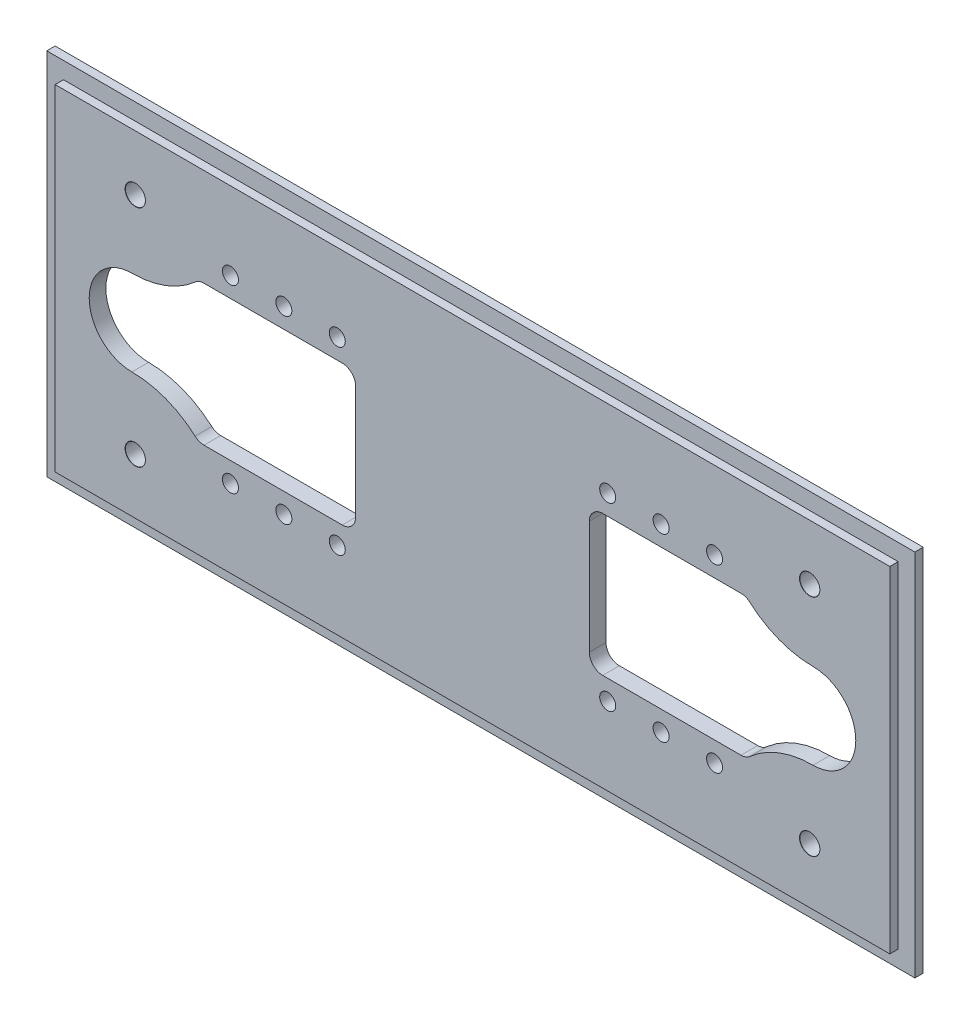
SolidWorks part; units mm, degrees
ref_plane "Plano frontal" through (0, 0, 0) normal (0, 0, 1) x (1, 0, 0)
ref_plane "Plano superior" through (0, 0, 0) normal (0, 1, 0) x (1, 0, 0)
ref_plane "Plano direito" through (0, 0, 0) normal (1, 0, 0) x (0, 0, -1)
sketch "Esboço1" plane through (0, 0, 0) normal (0, 0, 1) x (1, 0, 0)
  line L1 (-63.2916, 33.3513) -> (66.7084, 33.3513)
  line L2 (-63.2916, 33.3513) -> (-63.2916, -21.8987)
  line L3 (-63.2916, -21.8987) -> (66.7084, -21.8987)
  line L4 (66.7084, 33.3513) -> (66.7084, -21.8987)
  dimension "D1" = 130
  dimension "D2" = 55.25
extrude "Ressalto-extrusão1" add sketch "Esboço1" along normal blind 2.5
sketch "Esboço2" plane through (0, 0, 2.5) normal (0, 0, 1) x (1, 0, 0)
  line L0 (1.7084, 33.3513) -> (1.7084, -21.8987) construction
  line L1 (66.7084, 33.3513) -> (-63.2916, 33.3513) construction
  line L2 (-63.2916, -21.8987) -> (66.7084, -21.8987) construction
  line L11 (-54.581, 33.3513) -> (-54.581, -21.8987) construction
  line L13 (-63.2916, 33.3513) -> (66.7084, 33.3513)
  line L14 (-63.2916, 33.3513) -> (-63.2916, -21.8987)
  line L15 (-63.2916, -21.8987) -> (66.7084, -21.8987)
  line L16 (66.7084, 33.3513) -> (66.7084, -21.8987)
  line L17 (-60.7916, 30.8513) -> (64.2084, 30.8513)
  line L18 (-60.7916, 30.8513) -> (-60.7916, -19.3987)
  line L19 (-60.7916, -19.3987) -> (64.2084, -19.3987)
  line L20 (64.2084, 30.8513) -> (64.2084, -19.3987)
  dimension "D1" = 2.5
  dimension "D2" = 2.5
  dimension "D3" = 2.5
  dimension "D4" = 2.5
extrude "Corte-extrusão1" cut sketch "Esboço2" against normal blind 1.25
sketch "Esboço3" plane through (0, 0, 2.5) normal (0, 0, 1) x (1, 0, 0)
  line L0 (-48.7916, 30.8513) -> (-48.7916, -19.3987) construction
  line L1 (64.2084, 30.8513) -> (-60.7916, 30.8513) construction
  line L2 (-60.7916, -19.3987) -> (64.2084, -19.3987) construction
  line L3 (-60.7916, 30.8513) -> (-60.7916, -19.3987) construction
  line L4 (1.7084, 30.8513) -> (1.7084, -19.3987) construction
  line L5 (-60.7916, 5.7263) -> (1.7084, 5.7263) construction
  circle A0 centre (-48.7916, 22.5513) radius 2.75
  circle A1 centre (-48.7916, -11.0987) radius 2.75
  circle A2 centre (52.2084, -11.0987) radius 2.75
  circle A3 centre (52.2084, 22.5513) radius 2.75
  point P14 (-48.7916, 19.8013)
  dimension "D2" = 11.05
  dimension "D1" = 12
hole_wizard "Furos-guia com Ø3.0mm2" positions "Esboço4" profile "Esboço5" hole size "Ø3.0" standard "ISO" end condition through all
sketch "Esboço4" plane through (0, 0, 2.5) normal (0, 0, 1) x (1, 0, 0)
  point P0 (-48.7916, 22.5513)
  point P3 (-48.7916, -11.0987)
  point P6 (52.2084, -11.0987)
  point P9 (52.2084, 22.5513)
sketch "Esboço5" plane through (-48.7916, 22.5513, 2.5) normal (1, 0, 0) x (0, -1, 0)
  line L0 (0, 0) -> (0, 2.5)
  line L1 (0, 2.5) -> (1.5, 2.5)
  line L2 (1.5, 2.5) -> (1.5, 0.025)
  line L3 (1.5, 0.025) -> (1.525, 0)
  line L5 (1.525, 0) -> (0, 0)
  line L6 (-1.5, 0.025) -> (-1.525, 0) construction
  line L11 (0, -6.35) -> (0, 107.95) construction
  dimension "Thru Hole Dia." = 3
  dimension "Thru Hole Depth" = 2.5
  dimension "Near C'Sink Dia." = 3.05
  dimension "Near C'Sink Angle" = 90
sketch "Sketch1" plane through (0, 0, 2.5) normal (0, 0, 1) x (1, 0, 0)
  line L0 (-13.7916, 0.9763) -> (-13.7916, 10.4763) construction
  line L6 (-39.2916, -4.7737) -> (-15.7916, -4.7737)
  line L8 (-39.2916, 16.2263) -> (-15.7916, 16.2263)
  line L11 (-15.7916, -4.7737) -> (-15.7916, 16.2263)
  line L17 (-23.4916, -4.2737) -> (-17.0916, -4.2737) construction
  line L18 (-16.7916, -3.9737) -> (-16.7916, 1.4263) construction
  line L19 (-37.2916, 6.2263) -> (-37.2916, 15.5263) construction
  line L20 (1.7084, -19.3987) -> (1.7084, 30.8513) construction
  arc A22 (-49.2916, 12.1263) -> (-49.2916, -0.6737) centre (-49.2916, 5.7263) ccw
  arc A26 (-39.2916, -4.7737) -> (-49.2916, -0.6737) centre (-49.2916, -14.9188) ccw
  arc A27 (-39.2916, 16.2263) -> (-49.2916, 12.1263) centre (-49.2916, 26.3714) cw
  circle A28 centre (-49.2916, 5.7263) radius 5.4 construction
  point P9 (-13.7916, 5.7263)
  point P10 (-15.7916, 5.7263)
  dimension "D1" = 1
  dimension "D2" = 0.5
  dimension "D3" = 1
  dimension "D4" = 2
extrude "Cut-Extrude1" cut sketch "Sketch1" against normal blind 10
fillet "Filete1" radius 2 4 edges at (-15.7916, -4.7737, 1.25) (-39.2916, -4.7737, 1.25) (-15.7916, 16.2263, 1.25) (-39.2916, 16.2263, 1.25)
hole_wizard "Furo com folga de M21" positions "Esboço6" profile "Esboço7" hole size "M2" standard "DIN" end condition up to next
sketch "Esboço6" plane through (0, 0, 2.5) normal (0, 0, 1) x (1, 0, 0)
  circle A0 centre (37.9584, -7.7737) radius 1.25 construction
  point P0 (37.9584, -7.7737)
sketch "Esboço7" plane through (37.9584, -7.7737, 2.5) normal (1, 0, 0) x (0, -1, 0)
  line L0 (0, 0) -> (0, 2.5)
  line L1 (0, 2.5) -> (1.2, 2.5)
  line L2 (1.2, 2.5) -> (1.2, 0)
  line L5 (1.2, 0) -> (0, 0)
  line L11 (0, -6.35) -> (0, 107.95) construction
  dimension "Thru Hole Dia." = 2.4
  dimension "Thru Hole Depth" = 2.5
pattern_linear "Padrão linear1" count 3 spacing 8 along (-1, 0, 0) of "Furo com folga de M21"
ref_plane "Plano1" through (0, 5.7263, 0) normal (0, -1, 0) x (-1, 0, 0)
ref_plane "Plano2" through (1.7084, 0, 0) normal (1, 0, 0) x (0, 0, -1)
mirror "Espelhar1" about plane through (0, 5.7263, 0) normal (0, -1, 0) of "Padrão linear1", "Furo com folga de M21"
mirror "Espelhar2" about plane through (1.7084, 0, 0) normal (1, 0, 0) of "Filete1", "Espelhar1", "Cut-Extrude1", "Furo com folga de M21", "Padrão linear1"
